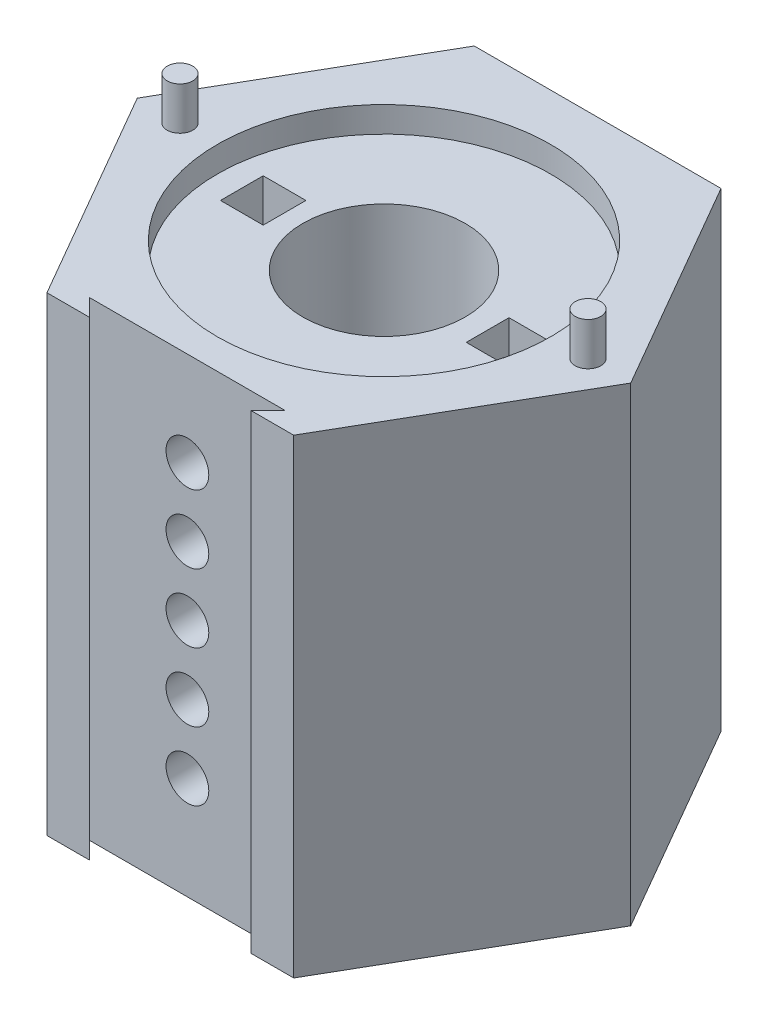
SolidWorks part; units mm, degrees
ref_plane "Front Plane" through (0, 0, 0) normal (0, 0, 1) x (1, 0, 0)
ref_plane "Top Plane" through (0, 0, 0) normal (0, 1, 0) x (1, 0, 0)
ref_plane "Right Plane" through (0, 0, 0) normal (1, 0, 0) x (0, 0, -1)
sketch "Sketch1" plane through (0, 0, 0) normal (0, 1, 0) x (1, 0, 0)
  line L1 (-28.8675, 0) -> (-14.4338, -25)
  line L2 (-14.4338, -25) -> (14.4338, -25)
  line L3 (14.4338, -25) -> (28.8675, 0)
  line L4 (28.8675, 0) -> (14.4338, 25)
  line L5 (14.4338, 25) -> (-14.4338, 25)
  line L6 (-14.4338, 25) -> (-28.8675, 0)
  circle A0 centre (0, 0) radius 25 construction
  dimension "D1" = 25
extrude "Boss-Extrude1" add sketch "Sketch1" along normal blind 55
sketch "Sketch2" plane through (0, 0, 0) normal (0, -1, 0) x (1, 0, 0)
  circle A0 centre (0, 0) radius 9.5
  dimension "D1" = 19
extrude "Cut-Extrude1" cut sketch "Sketch2" against normal blind 60
sketch "Sketch3" plane through (0, 55, 0) normal (0, 1, 0) x (1, 0, 0)
  circle A0 centre (0, 0) radius 19.5
  circle A1 centre (0, 0) radius 9.5 construction
  dimension "D1" = 10
extrude "Cut-Extrude2" cut sketch "Sketch3" against normal blind 3
sketch "Sketch4" plane through (0, 0, 25) normal (0, 0, 1) x (1, 0, 0)
  line L0 (-14.4338, 0) -> (14.4338, 0) construction
  circle A0 centre (0, 12) radius 2.5
  circle A1 centre (0, 20) radius 2.5
  circle A2 centre (0, 28) radius 2.5
  circle A3 centre (0, 36) radius 2.5
  circle A4 centre (0, 44) radius 2.5
  dimension "D1" = 5
  dimension "D2" = 5
  dimension "D3" = 5
  dimension "D4" = 5
  dimension "D5" = 5
  dimension "D6" = 8
  dimension "D7" = 8
  dimension "D8" = 8
  dimension "D9" = 8
  dimension "D10" = 12
extrude "Cut-Extrude3" cut sketch "Sketch4" against normal blind 23
sketch "Sketch5" plane through (0, 52, 0) normal (0, 1, 0) x (1, 0, 0)
  line L1 (-16.6346, 2.5) -> (-11.6346, 2.5)
  line L2 (-16.6346, 2.5) -> (-16.6346, -2.5)
  line L3 (-16.6346, -2.5) -> (-11.6346, -2.5)
  line L4 (-11.6346, 2.5) -> (-11.6346, -2.5)
  line L5 (-16.6346, 2.5) -> (-11.6346, -2.5) construction
  line L6 (-16.6346, -2.5) -> (-11.6346, 2.5) construction
  line L7 (12.1236, 2.5) -> (17.1236, 2.5)
  line L8 (12.1236, 2.5) -> (12.1236, -2.5)
  line L9 (12.1236, -2.5) -> (17.1236, -2.5)
  line L10 (17.1236, 2.5) -> (17.1236, -2.5)
  line L11 (12.1236, 2.5) -> (17.1236, -2.5) construction
  line L12 (12.1236, -2.5) -> (17.1236, 2.5) construction
  point P0 (-14.1346, 0)
  point P5 (14.6236, 0)
  dimension "D1" = 5
  dimension "D2" = 5
  dimension "D3" = 5
  dimension "D4" = 5
  dimension "D5" = 0
  dimension "D6" = 0
extrude "Cut-Extrude4" cut sketch "Sketch5" against normal blind 5
sketch "Sketch6" plane through (0, 0, 0) normal (0, -1, 0) x (1, 0, 0)
  line L0 (-14.4338, 25) -> (14.4338, 25) construction
  line L1 (-9.4338, 25) -> (9.4338, 25)
  line L3 (-9.4338, 23) -> (9.4338, 23)
  line L5 (-11.4338, 23) -> (11.4338, 23)
  line L6 (11.4338, 23) -> (9.4338, 25)
  line L7 (-11.4338, 23) -> (-9.4338, 25)
  line M6 (14.4338, 25) -> (-14.4338, 25)
  dimension "D1" = 5
  dimension "D2" = 5
  dimension "D3" = 2
  dimension "D4" = 2
  dimension "D5" = 2
extrude "Cut-Extrude5" cut sketch "Sketch6" against normal blind 60 contours L7 L5 L3 L6 M6
sketch "Sketch7" plane through (0, 55, 0) normal (0, 1, 0) x (1, 0, 0)
  circle A0 centre (23.8675, 0) radius 1.5
  circle A1 centre (-23.8675, 0) radius 1.5
  dimension "D1" = 3
  dimension "D2" = 3
  dimension "D3" = 5
  dimension "D4" = 5
extrude "Boss-Extrude2" add sketch "Sketch7" along normal blind 5
